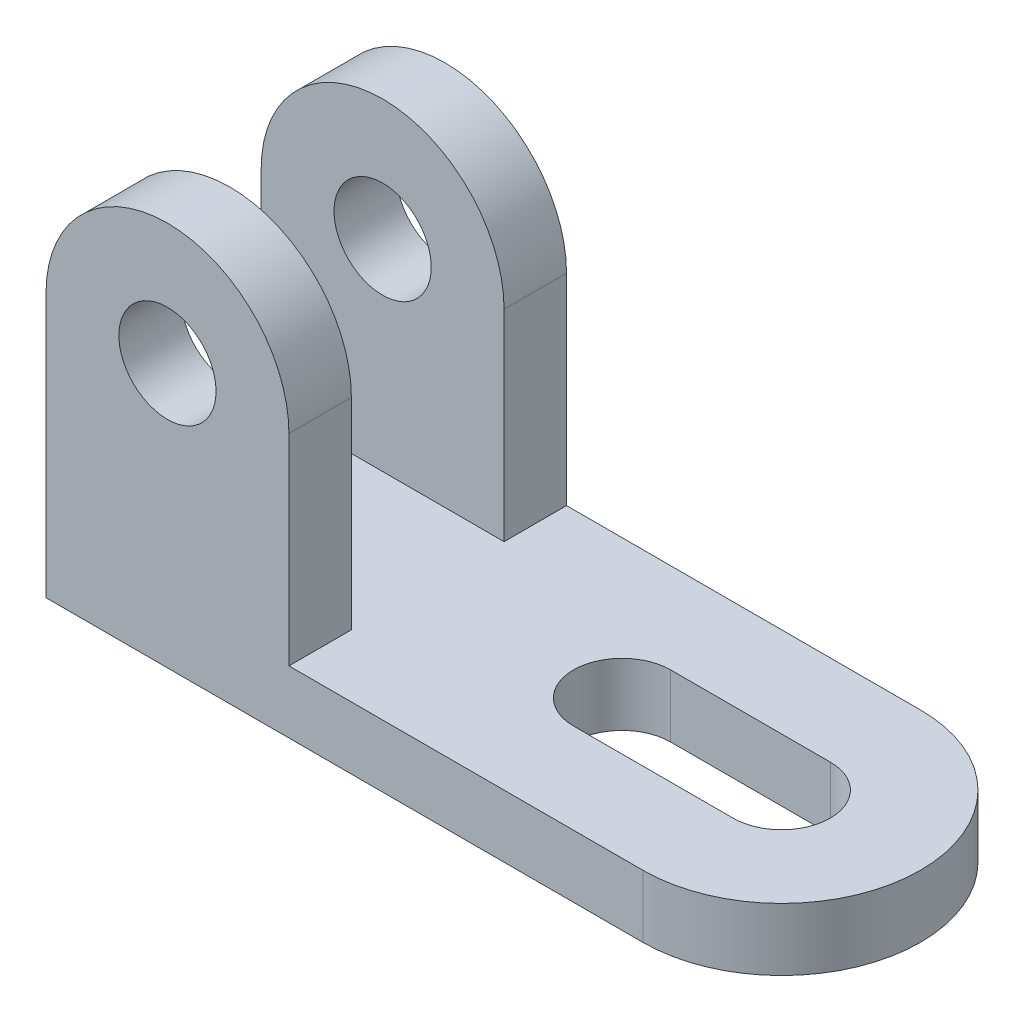
SolidWorks part; units mm, degrees
ref_plane "Front Plane" through (0, 0, 0) normal (0, 0, 1) x (1, 0, 0)
ref_plane "Top Plane" through (0, 0, 0) normal (0, 1, 0) x (1, 0, 0)
ref_plane "Right Plane" through (0, 0, 0) normal (1, 0, 0) x (0, 0, -1)
sketch "Sketch2" plane through (0, 0, 0) normal (0, 1, 0) x (1, 0, 0)
  line L0 (-23, 7) -> (0, 7)
  line L1 (-23, -7) -> (0, -7)
  line L2 (0, -20) -> (-86, -20)
  line L3 (0, 20) -> (-86, 20)
  line L4 (-86, 20) -> (-86, -20)
  line L5 (20, 0) -> (-86, 0) construction
  arc A0 (0, -7) -> (0, 7) centre (0, 0) ccw
  arc A1 (-23, 7) -> (-23, -7) centre (-23, 0) ccw
  arc A3 (0, -20) -> (0, 20) centre (0, 0) ccw
  dimension "D1" = 23
  dimension "D2" = 14
  dimension "D3" = 14
  dimension "D4" = 86
  dimension "D5" = 20
  dimension "D6" = 14
extrude "Boss-Extrude1" add sketch "Sketch2" along normal blind 9
sketch "Sketch3" plane through (0, 0, 20) normal (0, 0, 1) x (1, 0, 0)
  line L0 (-86, 0) -> (-86, 38)
  line L1 (-51, 38) -> (-51, 0)
  line L2 (-86, 0) -> (0, 0) construction
  line L3 (-51, 0) -> (-86, 0)
  circle A0 centre (-68.5, 38) radius 17.5
  circle A1 centre (-68.5, 38) radius 7
  line M1 (-86, 0) -> (0, 0)
  line M3 (0, 9) -> (-86, 9)
  line M4 (-86, 9) -> (-86, 0)
  dimension "D1" = 35
  dimension "D2" = 14
extrude "Boss-Extrude2" add sketch "Sketch3" against normal blind 9 contours A0 L0 L1 M3 | L1 M3 M4 M1 | A0 A1
mirror "Mirror1" about plane through (0, 0, 0) normal (0, 0, 1) of "Boss-Extrude2", "Boss-Extrude1"
